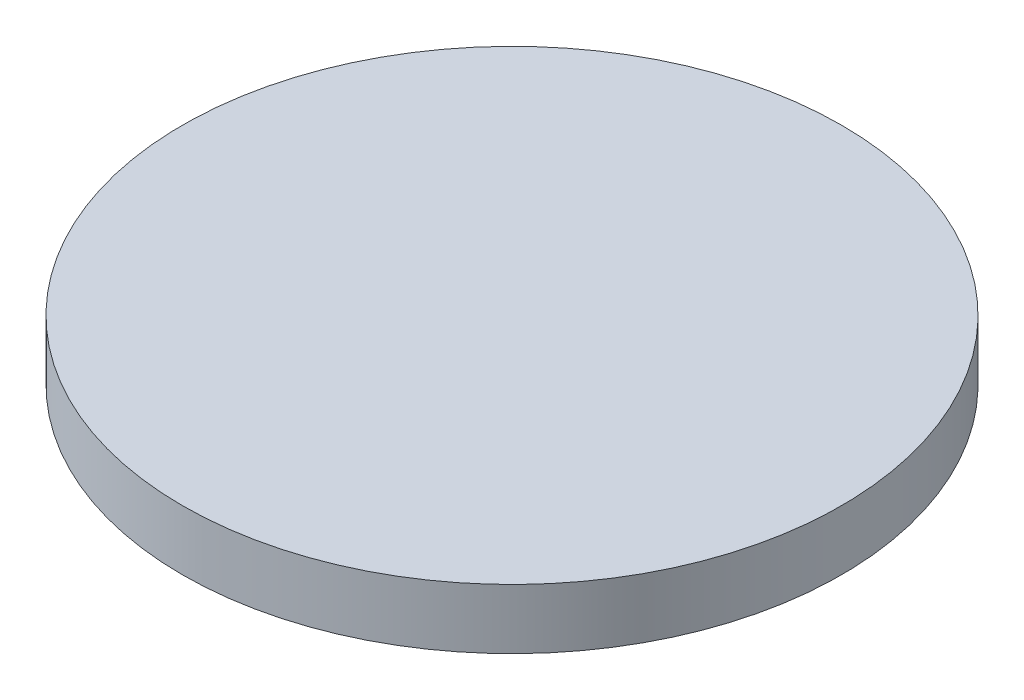
SolidWorks part; units mm, degrees
ref_plane "Front Plane" through (0, 0, 0) normal (0, 0, 1) x (1, 0, 0)
ref_plane "Top Plane" through (0, 0, 0) normal (0, 1, 0) x (1, 0, 0)
ref_plane "Right Plane" through (0, 0, 0) normal (1, 0, 0) x (0, 0, -1)
sketch "Sketch1" plane through (0, 0, 0) normal (0, 1, 0) x (1, 0, 0)
  circle A0 centre (0, 0) radius 0.55
  dimension "D1" = 1.1
extrude "Boss-Extrude1" add sketch "Sketch1" along normal blind 0.1
